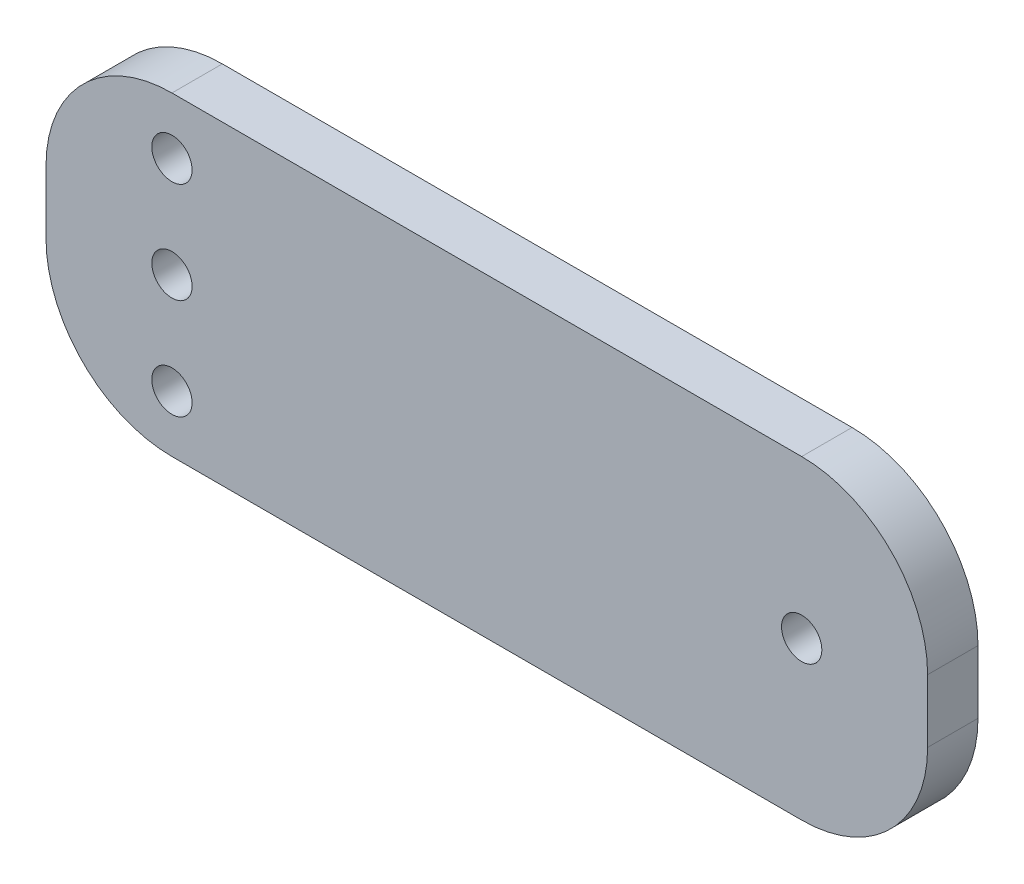
SolidWorks part; units mm, degrees
ref_plane "前视基准面" through (0, 0, 0) normal (0, 0, 1) x (1, 0, 0)
ref_plane "上视基准面" through (0, 0, 0) normal (0, 1, 0) x (1, 0, 0)
ref_plane "右视基准面" through (0, 0, 0) normal (1, 0, 0) x (0, 0, -1)
sketch "草图1" plane through (0, 0, 0) normal (0, 0, 1) x (1, 0, 0)
  line L0 (-35, 0) -> (35, 0) construction
  line L1 (-35, -12.5) -> (35, -12.5)
  line L2 (-35, -12.5) -> (-35, 12.5)
  line L3 (-35, 12.5) -> (35, 12.5)
  line L4 (35, -12.5) -> (35, 12.5)
  line L5 (-35, -12.5) -> (35, 12.5) construction
  line L6 (-35, 12.5) -> (35, -12.5) construction
  line L7 (-25, 0) -> (-25, 16.6595) construction
  line L8 (-25, 16.6595) -> (-25, -14.4543) construction
  circle A0 centre (-25, 0) radius 1.6
  circle A1 centre (25, 0) radius 1.6
  circle A2 centre (-25, 0) radius 8 construction
  circle A3 centre (-25, 8) radius 1.6
  circle A4 centre (-25, -8) radius 1.6
  point P0 (0, 0)
  dimension "D3" = 3.2
  dimension "D4" = 10
  dimension "D5" = 3.2
  dimension "D6" = 10
  dimension "D7" = 16
  dimension "D1" = 70
  dimension "D2" = 25
extrude "凸台-拉伸1" add sketch "草图1" along normal blind 4
fillet "圆角1" radius 10 4 edges at (-35, 12.5, 2) (-35, -12.5, 2) (35, -12.5, 2) (35, 12.5, 2)
